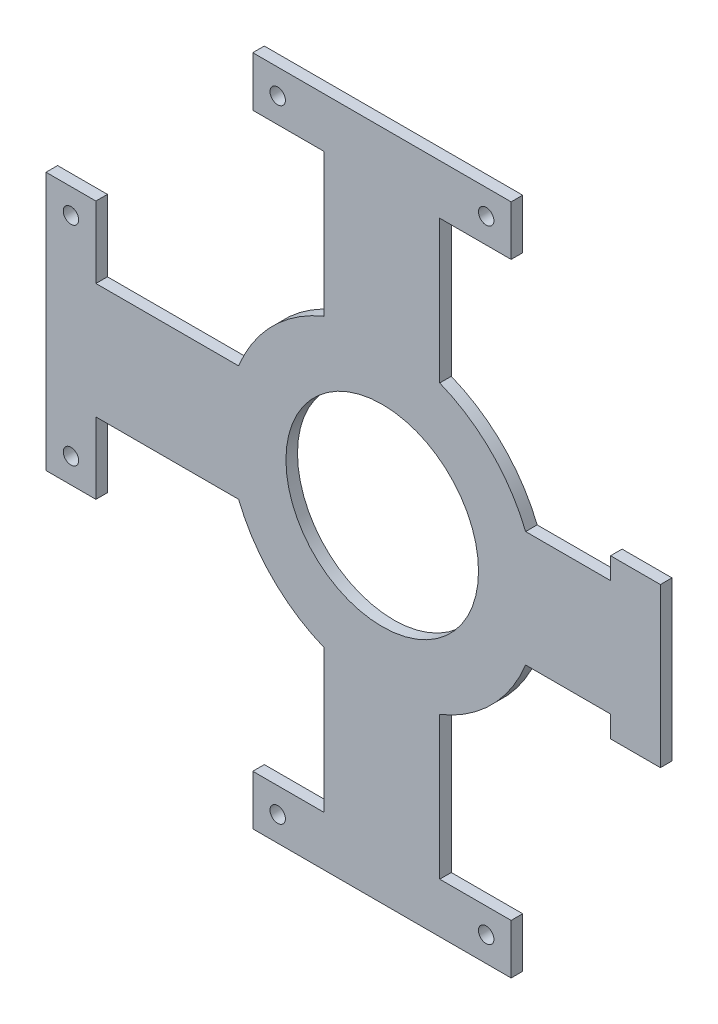
SolidWorks part; units mm, degrees
ref_plane "Alzado" through (0, 0, 0) normal (0, 0, 1) x (1, 0, 0)
ref_plane "Planta" through (0, 0, 0) normal (0, 1, 0) x (1, 0, 0)
ref_plane "Vista lateral" through (0, 0, 0) normal (1, 0, 0) x (0, 0, -1)
sketch "Croquis1" plane through (0, 0, 0) normal (0, 0, 1) x (1, 0, 0)
  line L0 (0, 0) -> (0, 37.2565) construction
  line L1 (-15.071, 74.3065) -> (-15.071, 37.2565)
  line L2 (-37.2851, 15) -> (-74.3351, 15)
  line L3 (-15.071, 37.2565) -> (14.929, 37.2565) construction
  line L4 (14.929, 37.2565) -> (14.929, 74.3065)
  line L5 (-15.071, 74.3065) -> (-20.661, 74.3065)
  line L6 (-25, 0) -> (25, 0) construction
  line L7 (0, 25) -> (0, -25) construction
  line L8 (-15.071, -37.2565) -> (-15.071, -74.3065)
  line L9 (14.929, -37.2565) -> (14.929, -74.3065)
  line L10 (14.929, 74.3065) -> (20.519, 74.3065)
  line L12 (-37.2851, -15) -> (-74.3351, -15)
  line L13 (-20.661, 74.3065) -> (-20.661, 87.2565)
  line L14 (-20.661, 87.2565) -> (20.519, 87.2565)
  line L15 (20.519, 87.2565) -> (20.519, 74.3065)
  line L16 (20.519, -87.2565) -> (20.519, -74.3065)
  line L17 (14.929, -74.3065) -> (20.519, -74.3065)
  line L18 (-20.661, -87.2565) -> (20.519, -87.2565)
  line L19 (-20.661, -74.3065) -> (-20.661, -87.2565)
  line L20 (-15.071, -74.3065) -> (-20.661, -74.3065)
  line L21 (-74.3351, -15) -> (-74.3351, -20.59)
  line L22 (-74.3351, -20.59) -> (-87.2851, -20.59)
  line L23 (-87.2851, -20.59) -> (-87.2851, 20.59)
  line L24 (-87.2851, 20.59) -> (-74.3351, 20.59)
  line L25 (-74.3351, 20.59) -> (-74.3351, 15)
  line L26 (37.228, 15) -> (59.278, 15)
  line L27 (37.228, -15) -> (59.278, -15)
  line L28 (59.278, -15) -> (59.278, -20.59)
  line L29 (59.278, -20.59) -> (72.228, -20.59)
  line L30 (72.228, -20.59) -> (72.228, 20.59)
  line L31 (72.228, 20.59) -> (59.278, 20.59)
  line L32 (59.278, 20.59) -> (59.278, 15)
  arc A0 (-15.071, 37.2565) -> (-37.2851, 15) centre (0, 0) ccw
  circle A1 centre (0, 0) radius 25
  arc A2 (-37.2851, -15) -> (-15.071, -37.2565) centre (0, 0) ccw
  arc A3 (14.929, 37.2565) -> (37.228, 15) centre (0, 0) cw
  arc A4 (14.929, -37.2565) -> (37.228, -15) centre (0, 0) ccw
  dimension "D1" = 50
  dimension "D2" = 5.59
  dimension "D3" = 37.05
  dimension "D4" = 5.59
  dimension "D5" = 12.95
  dimension "D6" = 37.05
  dimension "D7" = 37.05
  dimension "D8" = 5.59
  dimension "D9" = 5.59
  dimension "D10" = 12.95
  dimension "D11" = 37.05
  dimension "D12" = 37.05
  dimension "D13" = 22.05
  dimension "D14" = 5.59
  dimension "D15" = 22.05
  dimension "D16" = 5.59
  dimension "D17" = 12.95
  dimension "D18" = 12.95
  dimension "D19" = 30
  dimension "D20" = 12.95
  dimension "D21" = 41.18
extrude "Saliente-Extruir1" add sketch "Croquis1" along normal blind 3
sketch "Croquis2" plane through (0, 0, 0) normal (0, 0, -1) x (-1, 0, 0)
  line L1 (-20.519, 87.2565) -> (-33.469, 87.2565)
  line L2 (-20.519, 87.2565) -> (-20.519, 74.3065)
  line L3 (-20.519, 74.3065) -> (-33.469, 74.3065)
  line L4 (-33.469, 87.2565) -> (-33.469, 74.3065)
  line L5 (20.661, 87.2565) -> (33.611, 87.2565)
  line L6 (20.661, 87.2565) -> (20.661, 74.3065)
  line L7 (20.661, 74.3065) -> (33.611, 74.3065)
  line L8 (33.611, 87.2565) -> (33.611, 74.3065)
  line L9 (-20.519, -74.3065) -> (-33.469, -74.3065)
  line L10 (-20.519, -74.3065) -> (-20.519, -87.2565)
  line L11 (-20.519, -87.2565) -> (-33.469, -87.2565)
  line L12 (-33.469, -74.3065) -> (-33.469, -87.2565)
  line L13 (20.661, -74.3065) -> (33.611, -74.3065)
  line L14 (20.661, -74.3065) -> (20.661, -87.2565)
  line L15 (20.661, -87.2565) -> (33.611, -87.2565)
  line L16 (33.611, -74.3065) -> (33.611, -87.2565)
  line L17 (74.3351, 20.59) -> (87.2851, 20.59)
  line L18 (74.3351, 20.59) -> (74.3351, 33.54)
  line L19 (74.3351, 33.54) -> (87.2851, 33.54)
  line L20 (87.2851, 20.59) -> (87.2851, 33.54)
  line L21 (74.3351, -20.59) -> (87.2851, -20.59)
  line L22 (74.3351, -20.59) -> (74.3351, -33.54)
  line L23 (74.3351, -33.54) -> (87.2851, -33.54)
  line L24 (87.2851, -20.59) -> (87.2851, -33.54)
  dimension "D1" = 12.95
  dimension "D2" = 12.95
  dimension "D3" = 12.95
  dimension "D4" = 12.95
  dimension "D5" = 12.95
  dimension "D6" = 12.95
  dimension "D7" = 12.95
  dimension "D8" = 12.95
  dimension "D9" = 12.95
  dimension "D10" = 12.95
  dimension "D11" = 12.95
extrude "Saliente-Extruir2" add sketch "Croquis2" against normal blind 3
sketch "Croquis3" plane through (0, 0, 0) normal (0, 0, -1) x (-1, 0, 0)
  line L0 (-33.469, 74.3065) -> (-20.519, 74.3065) construction
  line L1 (-14.929, 74.3065) -> (-33.469, 74.3065) construction
  line L2 (-33.469, 74.3065) -> (-20.519, 87.2565) construction
  line L3 (33.611, 87.2565) -> (-33.469, 87.2565) construction
  line L4 (-20.519, -74.3065) -> (-20.519, -87.2565) construction
  line L5 (-14.929, -74.3065) -> (-33.469, -74.3065) construction
  line L6 (33.611, -87.2565) -> (-33.469, -87.2565) construction
  line L7 (33.611, 87.2565) -> (20.661, 87.2565) construction
  line L8 (20.661, 87.2565) -> (20.661, 74.3065) construction
  line L9 (15.071, 74.3065) -> (33.611, 74.3065) construction
  line L10 (33.611, -74.3065) -> (20.661, -74.3065) construction
  line L12 (-33.469, -74.3065) -> (-20.519, -87.2565) construction
  line L13 (15.071, -74.3065) -> (33.611, -74.3065) construction
  line L14 (20.661, 74.3065) -> (33.611, 74.3065) construction
  line L15 (33.611, 74.3065) -> (20.661, 87.2565) construction
  line L16 (87.2851, -33.54) -> (87.2851, -20.59) construction
  line L17 (87.2851, -33.54) -> (87.2851, 33.54) construction
  line L18 (87.2851, -20.59) -> (74.3351, -20.59) construction
  line L19 (74.3351, -15) -> (74.3351, -33.54) construction
  line L20 (87.2851, 33.54) -> (87.2851, 20.59) construction
  line L21 (87.2851, 20.59) -> (74.3351, 20.59) construction
  line L22 (74.3351, 33.54) -> (74.3351, 15) construction
  line L23 (87.2851, 20.59) -> (74.3351, 33.54) construction
  line L24 (74.3351, -33.54) -> (87.2851, -20.59) construction
  line L26 (-20.519, -74.3065) -> (-33.469, -74.3065) construction
  line L27 (-33.469, 87.2565) -> (-33.469, 74.3065) construction
  line L28 (33.611, 74.3065) -> (33.611, 87.2565) construction
  line L29 (87.2851, 33.54) -> (74.3351, 33.54) construction
  line L30 (74.3351, -33.54) -> (87.2851, -33.54) construction
  line L32 (-33.469, -74.3065) -> (-33.469, -87.2565) construction
  line L33 (20.661, -74.3065) -> (20.661, -87.2565) construction
  line L34 (20.661, -87.2565) -> (33.611, -74.3065) construction
  line L35 (33.611, -87.2565) -> (33.611, -74.3065) construction
  circle A0 centre (-26.994, 80.7815) radius 2
  circle A1 centre (27.136, 80.7815) radius 2
  circle A2 centre (27.136, -80.7815) radius 2
  circle A3 centre (-26.994, -80.7815) radius 2
  circle A4 centre (80.8101, -27.065) radius 2
  circle A5 centre (80.8101, 27.065) radius 2
  dimension "D1" = 4
  dimension "D2" = 4
  dimension "D3" = 4
  dimension "D4" = 4
  dimension "D5" = 4
  dimension "D6" = 4
  dimension "D7" = 6.475
  dimension "D8" = 6.475
  dimension "D9" = 6.475
  dimension "D10" = 6.475
  dimension "D11" = 6.475
  dimension "D12" = 6.475
extrude "Cortar-Extruir1" cut sketch "Croquis3" against normal through all
sketch "Croquis4" plane through (0, 0, 0) normal (0, 0, -1) x (-1, 0, 0)
  line L0 (25, 0) -> (-25, 0) construction
  circle A0 centre (0, 0) radius 25 construction
